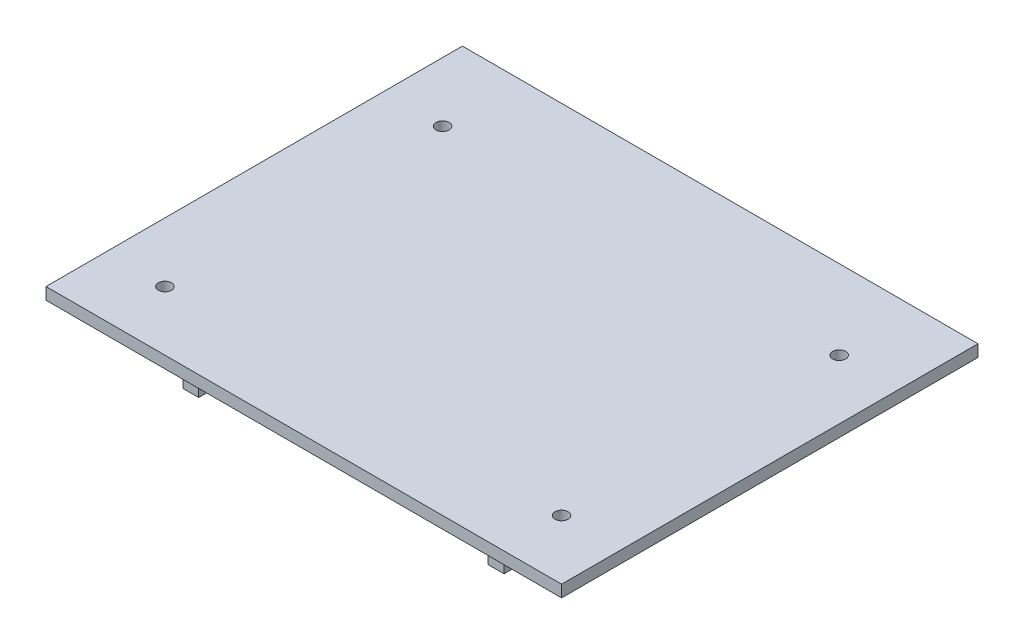
SolidWorks part; units mm, degrees
ref_plane "前视基准面" through (0, 0, 0) normal (0, 0, 1) x (1, 0, 0)
ref_plane "上视基准面" through (0, 0, 0) normal (0, 1, 0) x (1, 0, 0)
ref_plane "右视基准面" through (0, 0, 0) normal (1, 0, 0) x (0, 0, -1)
other "Configuration Table"
sketch "草图1" plane through (0, 0, 0) normal (0, 1, 0) x (1, 0, 0)
  line L1 (-65, 12) -> (65, 12)
  line L2 (-65, 12) -> (-65, -93)
  line L3 (-65, -93) -> (65, -93)
  line L4 (65, 12) -> (65, -93)
  dimension "D1" = 105
extrude "支架连接板_3mm" add sketch "草图1" along normal blind 3
sketch "草图2" plane through (0, 0, 0) normal (0, 1, 0) x (1, 0, 0)
  line L0 (-65, -93) -> (65, -93) construction
  line L1 (-40.5, 8) -> (-36.5, 8)
  line L2 (-40.5, 8) -> (-40.5, -83)
  line L3 (-40.5, -83) -> (-36.5, -83)
  line L4 (-36.5, 8) -> (-36.5, -83)
  line L5 (36.5, 8) -> (40.5, 8)
  line L6 (36.5, 8) -> (36.5, -83)
  line L7 (36.5, -83) -> (40.5, -83)
  line L8 (40.5, 8) -> (40.5, -83)
  line L9 (65, 12) -> (-65, 12) construction
  dimension "D1" = 4
  dimension "D2" = 36.5
  dimension "D3" = 4
  dimension "D4" = 36.5
  dimension "D5" = 10
  dimension "D6" = 4
  dimension "D7" = 4
  dimension "D8" = 10
extrude "左右导轨_12mm" add sketch "草图2" against normal blind 12
sketch "草图3" plane through (40.5, 0, 0) normal (1, 0, 0) x (0, 0, -1)
  line L0 (-20.4891, -5.5) -> (-72.1891, -5.5) construction
  line L1 (-20.4891, -7.15) -> (-72.1891, -7.15)
  line L2 (-20.4891, -3.85) -> (-72.1891, -3.85)
  circle A0 centre (0, -5.5) radius 1.65
  arc A1 (-20.4891, -7.15) -> (-20.4891, -3.85) centre (-20.4891, -5.5) ccw
  arc A2 (-72.1891, -3.85) -> (-72.1891, -7.15) centre (-72.1891, -5.5) ccw
  point P4 (-46.3391, -5.5)
  dimension "D1" = 3.3
  dimension "D2" = 51.7
extrude "左右铰接孔及滑槽_3p3mm" cut sketch "草图3" against normal through all
sketch "草图4" plane through (0, 3, 0) normal (0, 1, 0) x (1, 0, 0)
  line L0 (65, -93) -> (65, 12) construction
  line L1 (-65, 12) -> (-65, -93) construction
  circle A0 centre (-50, -8) radius 1.65
  circle A1 centre (-50, -78) radius 1.65
  circle A2 centre (50, -8) radius 1.65
  circle A3 centre (50, -78) radius 1.65
  dimension "D1" = 3.3
  dimension "D2" = 15
  dimension "D3" = 3.3
  dimension "D5" = 15
  dimension "D6" = 3.3
  dimension "D7" = 3.3
  dimension "D8" = 15
  dimension "D4" = 15
extrude "Cut-Extrude1" cut sketch "草图4" against normal through all
